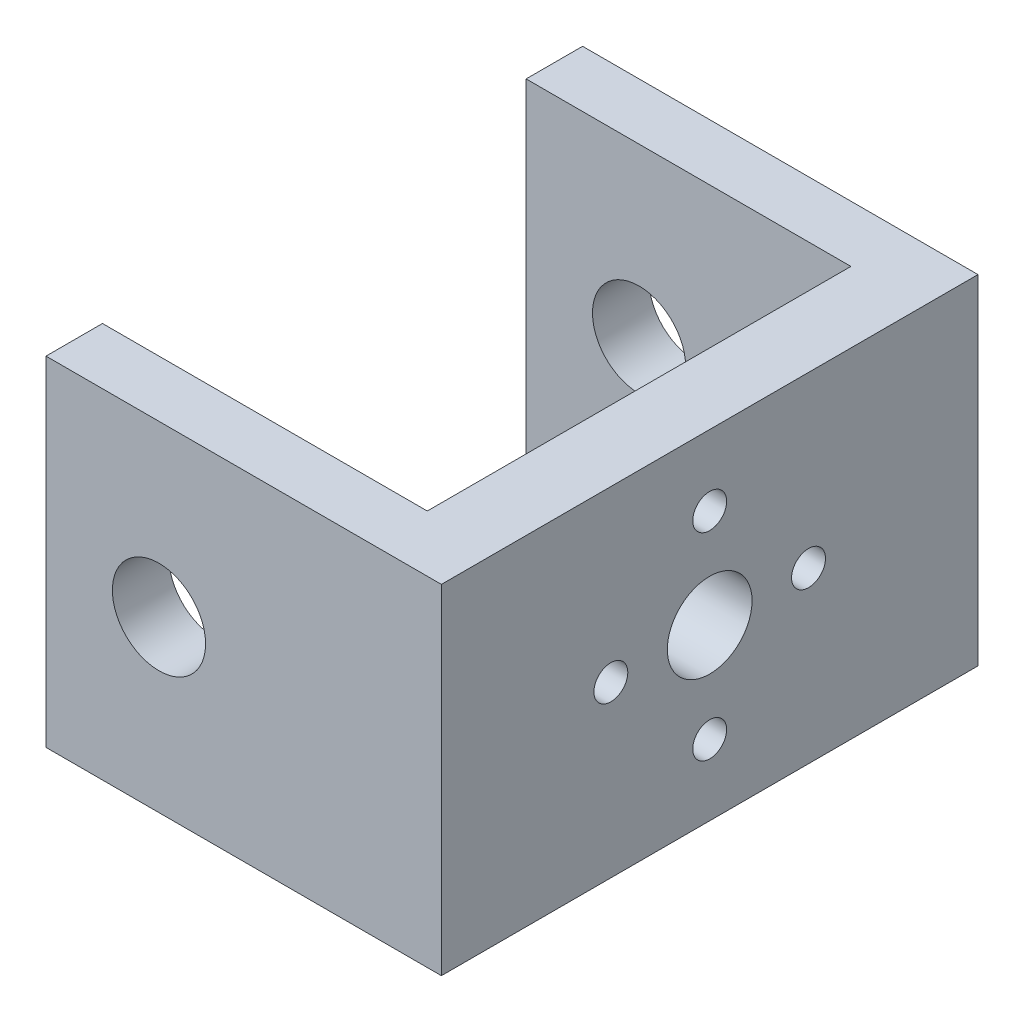
SolidWorks part; units mm, degrees
ref_plane "Front Plane" through (0, 0, 0) normal (0, 0, 1) x (1, 0, 0)
ref_plane "Top Plane" through (0, 0, 0) normal (0, 1, 0) x (1, 0, 0)
ref_plane "Right Plane" through (0, 0, 0) normal (1, 0, 0) x (0, 0, -1)
sketch "Sketch1" plane through (0, 0, 0) normal (0, 0, 1) x (1, 0, 0)
  line L1 (0, 0) -> (28, 0)
  line L2 (0, 0) -> (0, 24)
  line L3 (0, 24) -> (28, 24)
  line L4 (28, 0) -> (28, 24)
  dimension "D1" = 28
  dimension "D2" = 24
extrude "Boss-Extrude1" add sketch "Sketch1" along normal blind 4
sketch "Sketch3" plane through (0, 0, 0) normal (0, 0, -1) x (-1, 0, 0)
  line L0 (0, 0) -> (-28, 0) construction
  line L1 (-28, 24) -> (-23, 24)
  line L2 (-28, 24) -> (-28, 0)
  line L3 (-28, 0) -> (-23, 0)
  line L4 (-23, 24) -> (-23, 0)
  dimension "D1" = 5
extrude "Boss-Extrude2" add sketch "Sketch3" along normal blind 30
pattern_linear "LPattern1" count 2 spacing 34 along (0, 0, -1) of "Boss-Extrude1"
hole_wizard "M6 Clearance Hole1" positions "Sketch6" profile "Sketch7" hole size "M6" standard "ANSI Metric" end condition through all
sketch "Sketch6" plane through (0, 0, 4) normal (0, 0, 1) x (1, 0, 0)
  line L0 (23, 0) -> (23, 24) construction
  line L1 (0, 0) -> (28, 0) construction
  point P0 (8, 12)
  dimension "D1" = 15
  dimension "D2" = 12
sketch "Sketch7" plane through (8, 12, 4) normal (1, 0, 0) x (0, -1, 0)
  line L0 (0, 0) -> (0, 38)
  line L1 (0, 38) -> (3.3, 38)
  line L2 (3.3, 38) -> (3.3, 0)
  line L5 (3.3, 0) -> (0, 0)
  line L11 (0, -6.35) -> (0, 107.95) construction
  dimension "Thru Hole Dia." = 6.6
  dimension "Thru Hole Depth" = 38
sketch "Sketch8" plane through (28, 0, 0) normal (1, 0, 0) x (0, 0, -1)
  line L0 (-4, 24) -> (34, 24) construction
  line L1 (-4, 0) -> (-4, 24) construction
  circle A0 centre (15, 12) radius 3
  circle A1 centre (8, 12) radius 1.2
  point P8 (0, 0)
  point P9 (0, 0)
  point P10 (0, 0)
  point P11 (0, 0)
  dimension "D1" = 6
  dimension "D4" = 2.4
  dimension "D2" = 12
  dimension "D3" = 19
  dimension "D5" = 7
  dimension "D6" = 0
extrude "Cut-Extrude1" cut sketch "Sketch8" against normal up to next
pattern_circular "CirPattern1" count 4 over 360 about axis through (0, 12, -15) along (1, 0, 0) of "Cut-Extrude1"
